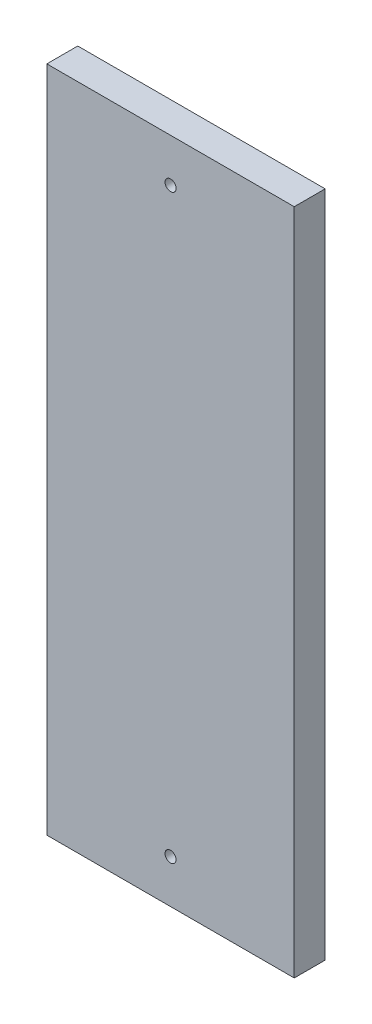
SolidWorks part; units mm, degrees
ref_plane "Front Plane" through (0, 0, 0) normal (0, 0, 1) x (1, 0, 0)
ref_plane "Top Plane" through (0, 0, 0) normal (0, 1, 0) x (1, 0, 0)
ref_plane "Right Plane" through (0, 0, 0) normal (1, 0, 0) x (0, 0, -1)
sketch "Sketch1" plane through (0, 0, 0) normal (0, 1, 0) x (1, 0, 0)
  line L1 (-25.4, 3.175) -> (25.4, 3.175)
  line L2 (-25.4, 3.175) -> (-25.4, -3.175)
  line L3 (-25.4, -3.175) -> (25.4, -3.175)
  line L4 (25.4, 3.175) -> (25.4, -3.175)
  line L5 (-25.4, 3.175) -> (25.4, -3.175) construction
  line L6 (-25.4, -3.175) -> (25.4, 3.175) construction
  point P0 (0, 0)
  dimension "D1" = 6.35
  dimension "D2" = 50.8
extrude "Boss-Extrude1" add sketch "Sketch1" along normal blind 137.16
sketch "Sketch2" plane through (0, 0, -3.175) normal (0, 0, -1) x (-1, 0, 0)
  line L0 (25.4, 68.58) -> (-25.4, 68.58) construction
  line L1 (25.4, 137.16) -> (25.4, 0) construction
  line L2 (-25.4, 137.16) -> (-25.4, 0) construction
  line L3 (-29.845, 118.11) -> (28.575, 118.11) construction
  circle A0 centre (0, 128.27) radius 1.1303
  circle A1 centre (0, 8.89) radius 1.1303
  dimension "D1" = 10.16
  dimension "D2" = 2.2606
extrude "Cut-Extrude1" cut sketch "Sketch2" against normal through all
